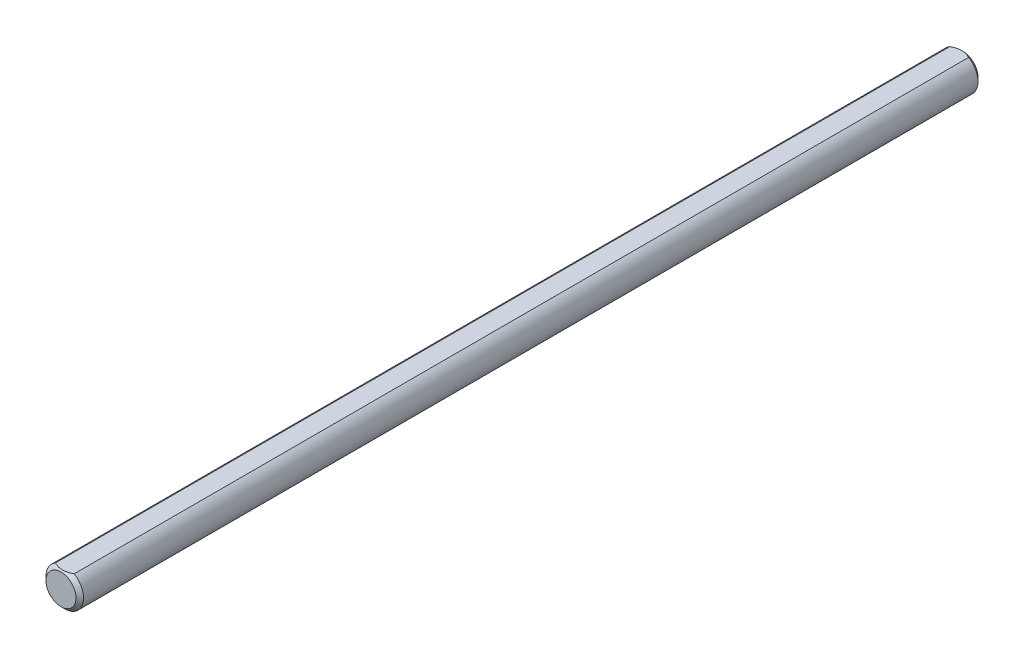
SolidWorks part; units mm, degrees
ref_plane "Front" through (0, 0, 0) normal (0, 0, 1) x (1, 0, 0)
ref_plane "Top" through (0, 0, 0) normal (0, 1, 0) x (1, 0, 0)
ref_plane "Right" through (0, 0, 0) normal (1, 0, 0) x (0, 0, -1)
sketch "Sketch1" plane through (0, 0, 0) normal (0, 0, 1) x (1, 0, 0)
  circle A0 centre (0, 0) radius 6.35
  dimension "D1" = 12.7
extrude "Extrude1" add sketch "Sketch1" along normal mid plane 304.8
chamfer "Chamfer1" distance 1.27 angle 45 2 edges at (6.35, 0, -152.4) (6.35, 0, 152.4)
sketch "Sketch13" plane through (0, 0, 0) normal (0, 0, 1) x (1, 0, 0)
  line L3 (-3.175, 5.4993) -> (3.175, 5.4993)
  circle A0 centre (0, 0) radius 6.35 construction
  arc A1 (3.175, 5.4993) -> (-3.175, 5.4993) centre (0, 0) ccw
  dimension "D1" = 6.35
extrude "Extrude7" cut sketch "Sketch13" against normal through all and the other way through all
equation "\"D1@Chamfer1\" = \"D1@Sketch1\" * .1"
equation "\"D1@Sketch13\" = \"D1@Sketch1\" * .5"
